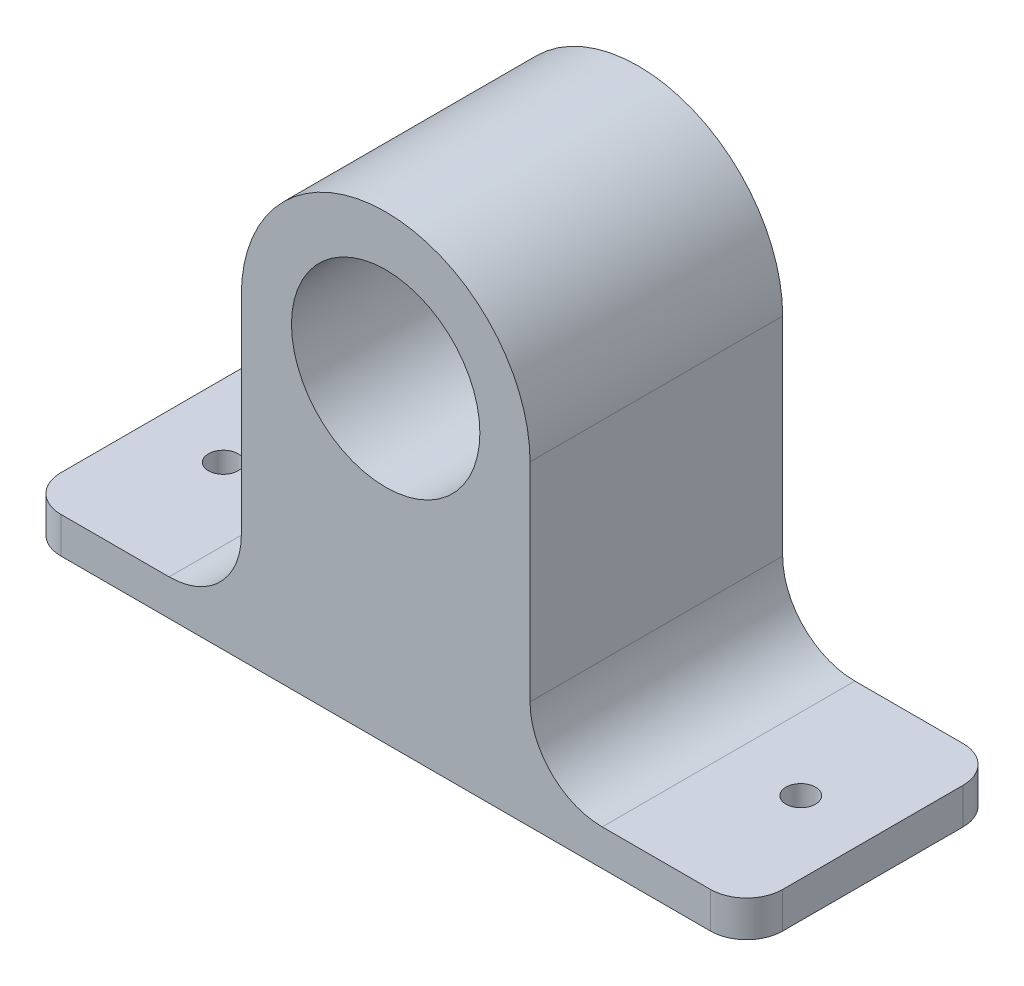
SolidWorks part; units mm, degrees
ref_plane "Alzado" through (0, 0, 0) normal (0, 0, 1) x (1, 0, 0)
ref_plane "Planta" through (0, 0, 0) normal (0, 1, 0) x (1, 0, 0)
ref_plane "Vista lateral" through (0, 0, 0) normal (1, 0, 0) x (0, 0, -1)
sketch "Croquis1" plane through (0, 0, 0) normal (0, 0, 1) x (1, 0, 0)
  line L0 (-20, 2.5) -> (-20, 41.3)
  line L1 (-50, 2.5) -> (-20, 2.5)
  line L2 (-50, 2.5) -> (-50, -2.5)
  line L3 (-50, -2.5) -> (50, -2.5)
  line L4 (50, 2.5) -> (50, -2.5)
  line L5 (-50, 2.5) -> (50, -2.5) construction
  line L6 (-50, -2.5) -> (50, 2.5) construction
  line L11 (-0.8589, -2.5) -> (17.5101, 50.9641) construction
  line L12 (-17.5101, 50.9641) -> (0.8589, -2.5) construction
  line L13 (20, 2.5) -> (20, 41.3)
  line L14 (-0.8589, 2.5) -> (0.8589, 2.5)
  line L15 (20, 2.5) -> (50, 2.5)
  circle A0 centre (0, 41.3) radius 13.05
  arc A1 (20, 41.3) -> (-20, 41.3) centre (0, 41.3) ccw
  point P0 (0, 0)
  point P5 (0, 0)
  dimension "D6" = 43.8
  dimension "D7" = 20
  dimension "D8" = 26.1
  dimension "D3" = 40
  dimension "D1" = 5
  dimension "D2" = 100
  dimension "D5" = 30
extrude "Saliente-Extruir1" add sketch "Croquis1" along normal blind 35
fillet "Redondeo1" radius 10 2 edges at (-20, 2.5, 17.5) (20, 2.5, 17.5)
fillet "Redondeo2" radius 5 4 edges at (-50, 0, 0) (-50, 0, 35) (50, 0, 0) (50, 0, 35)
sketch "Croquis2" plane through (0, 2.5, 0) normal (0, 1, 0) x (1, 0, 0)
  line L0 (0, -56.8098) -> (0, 12.4587) construction
  line L1 (-45, -35) -> (-30, -35) construction
  line L2 (-50, -30) -> (-50, -5) construction
  circle A0 centre (-40, -17.5) radius 2.05
  circle A1 centre (40, -17.5) radius 2.05
  dimension "D1" = 4.1
  dimension "D2" = 17.5
  dimension "D3" = 10
extrude "Cortar-Extruir1" cut sketch "Croquis2" against normal through all
